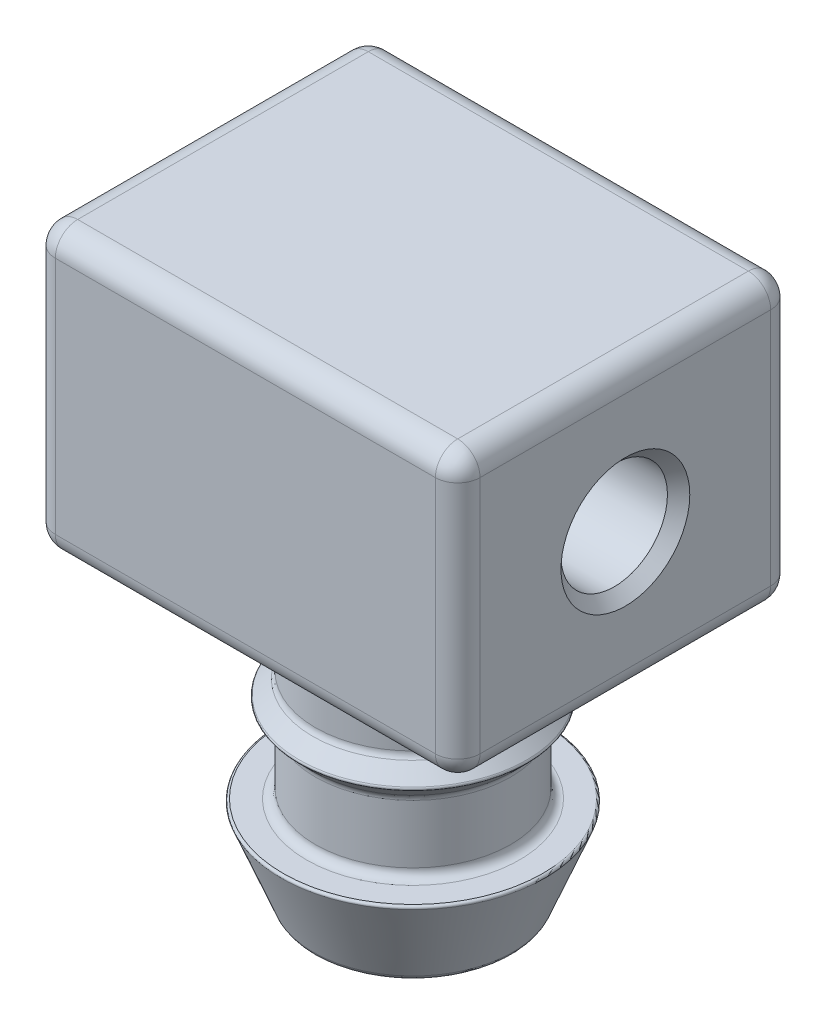
SolidWorks part; units mm, degrees
ref_plane "Front Plane" through (0, 0, 0) normal (0, 0, 1) x (1, 0, 0)
ref_plane "Top Plane" through (0, 0, 0) normal (0, 1, 0) x (1, 0, 0)
ref_plane "Right Plane" through (0, 0, 0) normal (1, 0, 0) x (0, 0, -1)
sketch "Sketch1" plane through (0, 0, 0) normal (0, 0, 1) x (1, 0, 0)
  line L0 (0, 7.7377) -> (0, -7.7377) construction
  line L1 (0, -12.7) -> (4.3656, -12.7)
  line L3 (4.3656, 0) -> (5.3975, 0)
  line L4 (5.3975, 0) -> (5.3975, 3.9688)
  line L5 (5.3975, 12.7) -> (0, 12.7)
  line L8 (0, 12.7) -> (0, -12.7)
  line L9 (4.3656, -12.7) -> (5.9531, -8.7312)
  line L21 (5.3975, 8.7312) -> (5.3975, 12.7)
  line L22 (5.3975, 0) -> (5.3975, 12.7) construction
  line L24 (5.3975, 8.7312) -> (3.81, 8.7312)
  line L25 (5.3975, 6.35) -> (0, 6.35) construction
  line L26 (3.81, 8.7312) -> (3.81, 3.9688)
  line L27 (3.81, 3.9688) -> (5.3975, 3.9688)
  line L32 (5.9531, -8.7312) -> (4.3656, -8.7312)
  line L33 (4.3656, -8.7312) -> (4.3656, -5.5563)
  line L34 (4.3656, -3.9687) -> (5.1594, -4.7625)
  line L35 (5.1594, -4.7625) -> (4.3656, -5.5563)
  line L36 (5.1594, -4.7625) -> (4.3656, -4.7625) construction
  line L37 (4.3656, -3.9687) -> (4.3656, 0)
  dimension "D7" = 1.5875
  dimension "D4" = 4.7625
  dimension "D1" = 12.7
  dimension "D2" = 3.9688
  dimension "D3" = 12.7
  dimension "D5" = 1.5875
  dimension "D6" = 10.795
  dimension "D8" = 8.7312
  dimension "D10" = 7.9375
  dimension "D11" = 45
  dimension "D9" = 0.7937
revolve "Revolve1" add sketch "Sketch1" angle 360 about L0
sketch "Sketch4" plane through (0, 12.7, 0) normal (0, 1, 0) x (1, 0, 0)
  line L1 (-9.5, -7.5) -> (9.5, -7.5)
  line L2 (-9.5, -7.5) -> (-9.5, 7.5)
  line L3 (-9.5, 7.5) -> (9.5, 7.5)
  line L4 (9.5, -7.5) -> (9.5, 7.5)
  line L5 (-9.5, -7.5) -> (9.5, 7.5) construction
  line L6 (-9.5, 7.5) -> (9.5, -7.5) construction
  point P0 (0, 0)
  dimension "D1" = 15
  dimension "D2" = 19
extrude "Boss-Extrude1" add sketch "Sketch4" against normal blind 12.7
sketch "Sketch2" plane through (0, 0, 0) normal (1, 0, 0) x (0, 0, -1)
  line L0 (0, 0) -> (0, 6.35) construction
  line L1 (-7.5, 12.7) -> (7.5, 12.7) construction
  line L2 (0, 6.35) -> (0, 12.7) construction
  line L4 (-7.5, 12.7) -> (7.5, 12.7) construction
  circle A0 centre (0, 6.35) radius 2.3813
  dimension "D1" = 4.7625
extrude "Cut-Extrude1" cut sketch "Sketch2" against normal through all both and the other way through all contours A0
sketch "Sketch3" plane through (0, 12.7, 0) normal (0, 1, 0) x (1, 0, 0)
  circle A0 centre (0, 0) radius 2.3813
  dimension "D1" = 4.7625
fillet "Fillet3" radius 0.3969 5 edges at (0, -12.7, 4.3656) (0, -8.7312, 4.3656) (0, 0, 4.3656) (0, -3.9687, 4.3656) (0, -5.5563, 4.3656)
fillet "Fillet4" radius 0.0992 2 edges at (0, -8.7313, 5.9531) (0, -4.7625, 5.1594)
chamfer "Chamfer1" distance 0.5 angle 45 2 edges at (9.5, 6.35, -2.3813) (-9.5, 6.35, -2.3813)
fillet "Fillet5" radius 1 12 edges at (0, 12.7, 7.5) (0, 0, 7.5) (-9.5, 12.7, 0) (-9.5, 0, 0) (9.5, 12.7, 0) (9.5, 0, 0) (-9.5, 6.35, -7.5) (0, 12.7, -7.5) (0, 0, -7.5) (9.5, 6.35, -7.5) (-9.5, 6.35, 7.5) (9.5, 6.35, 7.5)
